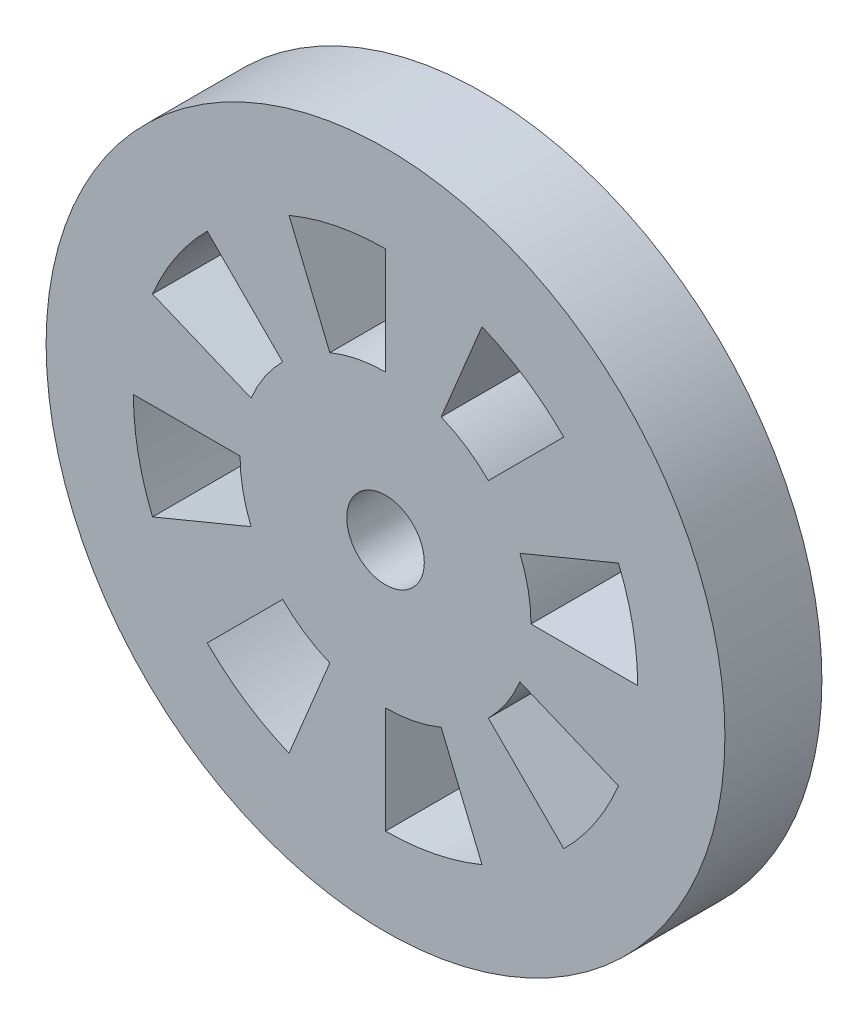
SolidWorks part; units mm, degrees
ref_plane "Front Plane" through (0, 0, 0) normal (0, 0, 1) x (1, 0, 0)
ref_plane "Top Plane" through (0, 0, 0) normal (0, 1, 0) x (1, 0, 0)
ref_plane "Right Plane" through (0, 0, 0) normal (1, 0, 0) x (0, 0, -1)
sketch "Sketch2" plane through (0, 0, 0) normal (0, 0, 1) x (1, 0, 0)
  circle A0 centre (0, 0) radius 3.5
extrude "Boss-Extrude1" add sketch "Sketch2" along normal blind 1
sketch "Sketch4" plane through (0, 0, 1) normal (0, 0, 1) x (1, 0, 0)
  circle A0 centre (0, 0) radius 0.4
extrude "Cut-Extrude2" cut sketch "Sketch4" against normal through all
sketch "Sketch5" plane through (0, 0, 1) normal (0, 0, 1) x (1, 0, 0)
  line L0 (0, 4.2445) -> (0, -4.196)
  line L3 (-4.7065, 0) -> (5.8321, 0)
  line L5 (-0.55, -1.5) -> (-0.55, -2.5)
  line L6 (-0.25, -1.5) -> (-0.25, -2.5)
  line L7 (-0.55, -2.5) -> (-0.25, -2.5)
  line L8 (-0.55, -1.5) -> (-0.25, -1.5)
  line L13 (0.55, -2.5) -> (0.25, -2.5)
  line L14 (0.55, -1.5) -> (0.55, -2.5)
  line L15 (0.55, -1.5) -> (0.25, -1.5)
  line L16 (0.25, -1.5) -> (0.25, -2.5)
  line L17 (-1.0607, -1.0607) -> (-1.8385, -1.8385)
  line L18 (0, 0) -> (2.4749, -2.4749)
  line L19 (-0.574, -1.3858) -> (-0.995, -2.4021)
  line L20 (0, 0) -> (1.3394, -3.2336)
  circle A0 centre (0, 0) radius 3.5 construction
  circle A3 centre (0, 0) radius 1.5
  circle A4 centre (0, 0) radius 2.6
extrude "Cut-Extrude3" cut sketch "Sketch5" against normal through all contours L17 A4 L19 A3
pattern_circular "CirPattern1" count 8 over 360 about axis through (0, 0, 0) along (0, 0, 1) of "Cut-Extrude3"
